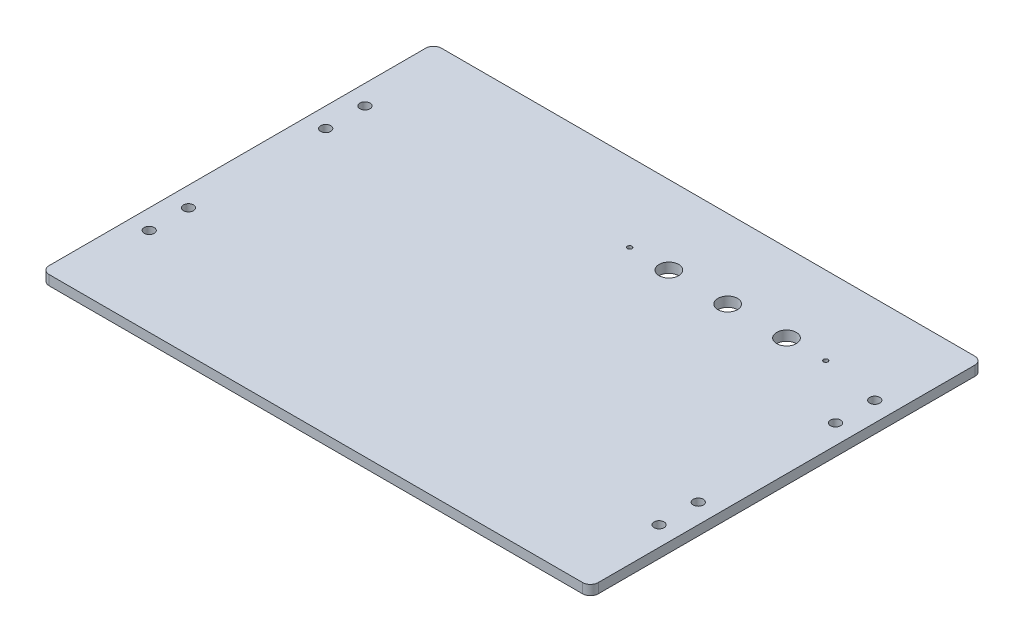
SolidWorks part; units mm, degrees
ref_plane "Front Plane" through (0, 0, 0) normal (0, 0, 1) x (1, 0, 0)
ref_plane "Top Plane" through (0, 0, 0) normal (0, 1, 0) x (1, 0, 0)
ref_plane "Right Plane" through (0, 0, 0) normal (1, 0, 0) x (0, 0, -1)
sketch "Sketch1" plane through (0, 0, 0) normal (0, 1, 0) x (1, 0, 0)
  line L1 (-177.8, 127) -> (177.8, 127)
  line L2 (-177.8, 127) -> (-177.8, -127)
  line L3 (-177.8, -127) -> (177.8, -127)
  line L4 (177.8, 127) -> (177.8, -127)
  line L5 (-177.8, 127) -> (177.8, -127) construction
  line L6 (-177.8, -127) -> (177.8, 127) construction
  point P0 (0, 0)
  dimension "D1" = 355.6
  dimension "D2" = 254
extrude "Boss-Extrude1" add sketch "Sketch1" along normal blind 6.35
sketch "Sketch2" plane through (0, 6.35, 0) normal (0, 1, 0) x (1, 0, 0)
  line L1 (-12.5, -62.3) -> (12.5, -62.3) construction
  line L2 (-12.5, -62.3) -> (-12.5, 87.7) construction
  line L3 (-12.5, 87.7) -> (12.5, 87.7) construction
  line L4 (12.5, -62.3) -> (12.5, 87.7) construction
  line L5 (-12.5, -62.3) -> (12.5, 87.7) construction
  line L6 (-12.5, 87.7) -> (12.5, -62.3) construction
  circle A0 centre (12.5, 87.7) radius 2.05
  circle A1 centre (12.5, -62.3) radius 2.05
  circle A2 centre (-12.5, -62.3) radius 2.05
  circle A3 centre (-12.5, 87.7) radius 2.05
  point P0 (0, 12.7)
  dimension "D1" = 25
  dimension "D3" = 4.1
  dimension "D2" = 150
  dimension "D4" = 0
  dimension "D5" = 12.7
extrude "Cut-Extrude1" [suppressed] cut sketch "Sketch2" against normal through all
sketch "Sketch3" [suppressed] plane through (0, 6.35, 0) normal (0, 1, 0) x (1, 0, 0)
  line L1 (-177.8, -127) -> (-152.4, -127)
  line L2 (-177.8, -127) -> (-177.8, -101.6)
  line L3 (-177.8, -101.6) -> (-152.4, -101.6)
  line L4 (-152.4, -127) -> (-152.4, -101.6)
  line L5 (-177.8, 127) -> (-152.4, 127)
  line L6 (-177.8, 127) -> (-177.8, 101.6)
  line L7 (-177.8, 101.6) -> (-152.4, 101.6)
  line L8 (-152.4, 127) -> (-152.4, 101.6)
  line L9 (177.8, 127) -> (152.4, 127)
  line L10 (177.8, 127) -> (177.8, 101.6)
  line L11 (177.8, 101.6) -> (152.4, 101.6)
  line L12 (152.4, 127) -> (152.4, 101.6)
  line L13 (177.8, -127) -> (152.4, -127)
  line L14 (177.8, -127) -> (177.8, -101.6)
  line L15 (177.8, -101.6) -> (152.4, -101.6)
  line L16 (152.4, -127) -> (152.4, -101.6)
  dimension "D1" = 25.4
extrude "Cut-Extrude2" [suppressed] cut sketch "Sketch3" against normal through all
sketch "Sketch4" plane through (0, 6.35, 0) normal (0, 1, 0) x (1, 0, 0)
  line L0 (-165.1, 69.85) -> (-165.1, 44.45) construction
  line L1 (-165.1, 44.45) -> (-165.1, -44.45) construction
  line L2 (-165.1, -44.45) -> (-165.1, -69.85) construction
  line L3 (-177.8, 127) -> (-177.8, -127) construction
  line L4 (0, 0) -> (0, 50.1151) construction
  line L5 (165.1, -44.45) -> (165.1, -69.85) construction
  line L6 (165.1, 44.45) -> (165.1, -44.45) construction
  line L7 (165.1, 69.85) -> (165.1, 44.45) construction
  circle A0 centre (-165.1, 69.85) radius 3.2639
  circle A1 centre (-165.1, 44.45) radius 3.2639
  circle A2 centre (-165.1, -44.45) radius 3.2639
  circle A3 centre (-165.1, -69.85) radius 3.2639
  circle A4 centre (165.1, -69.85) radius 3.2639
  circle A5 centre (165.1, -44.45) radius 3.2639
  circle A6 centre (165.1, 44.45) radius 3.2639
  circle A7 centre (165.1, 69.85) radius 3.2639
  point P8 (-165.1, 0)
  dimension "D1" = 6.5278
  dimension "D2" = 25.4
  dimension "D3" = 88.9
  dimension "D4" = 12.7
extrude "Cut-Extrude3" cut sketch "Sketch4" against normal through all
sketch "Sketch5" plane through (0, 6.35, 0) normal (0, 1, 0) x (1, 0, 0)
  line L0 (25.4, 76.2) -> (101.6, 76.2) construction
  line L1 (-177.8, 127) -> (177.8, 127) construction
  line L2 (177.8, 127) -> (177.8, -127) construction
  circle A0 centre (25.4, 76.2) radius 6.35
  circle A1 centre (63.5, 76.2) radius 6.35
  circle A2 centre (101.6, 76.2) radius 6.35
  point P7 (63.5, 76.2)
  dimension "D1" = 12.7
  dimension "D2" = 50.8
  dimension "D3" = 76.2
  dimension "D4" = 76.2
extrude "Switch Mounting" cut sketch "Sketch5" against normal through all
sketch "Sketch6" plane through (0, 6.35, 0) normal (0, 1, 0) x (1, 0, 0)
  circle A0 centre (127, 76.2) radius 1.4605
  circle A1 centre (0, 76.2) radius 1.4605
  point P5 (63.5, 76.2)
  dimension "D3" = 2.921
  dimension "D1" = 63.5
  dimension "D2" = 63.5
extrude "Cut-Extrude4" cut sketch "Sketch6" against normal through all
fillet "Fillet1" [suppressed] radius 5.08
fillet "Fillet2" radius 5.08 4 edges at (-177.8, 3.175, -127) (177.8, 3.175, -127) (177.8, 3.175, 127) (-177.8, 3.175, 127)
